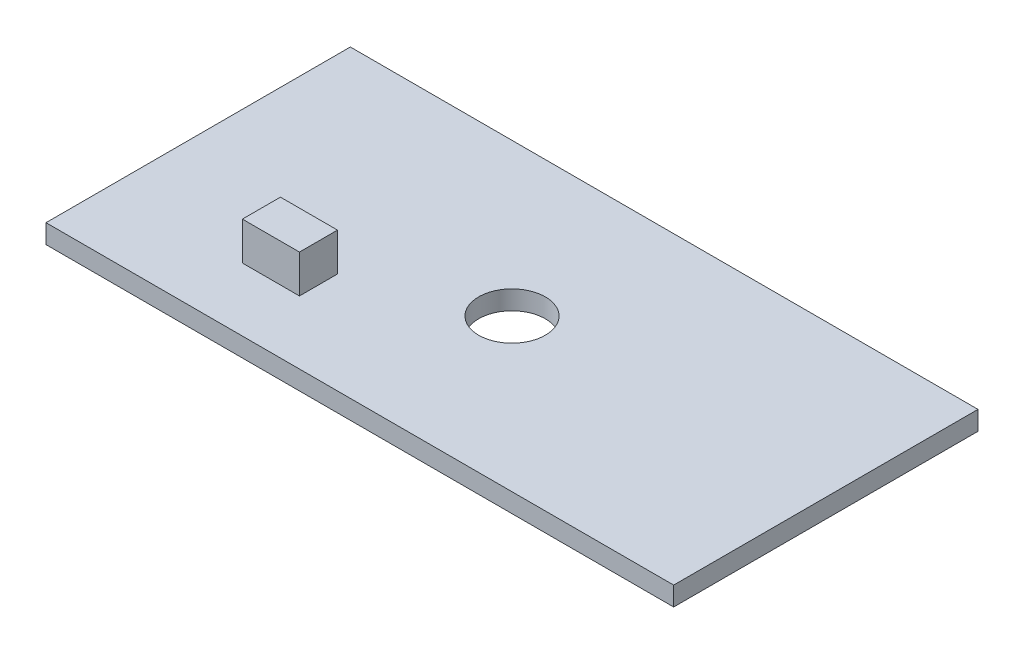
SolidWorks part; units mm, degrees
ref_plane "Спереди" through (0, 0, 0) normal (0, 0, 1) x (1, 0, 0)
ref_plane "Сверху" through (0, 0, 0) normal (0, 1, 0) x (1, 0, 0)
ref_plane "Справа" through (0, 0, 0) normal (1, 0, 0) x (0, 0, -1)
sketch "Эскиз1" plane through (0, 0, 0) normal (0, 1, 0) x (1, 0, 0)
  line L0 (-33, 0) -> (0, 0) construction
  line L1 (0, 8) -> (-33, 8)
  line L2 (0, 8) -> (0, -8)
  line L3 (0, -8) -> (-33, -8)
  line L4 (-33, 8) -> (-33, -8)
  circle A0 centre (-16.5, 0) radius 1.75
  dimension "D3" = 3.5
  dimension "D1" = 16
  dimension "D2" = 33
extrude "Бобышка-Вытянуть1" add sketch "Эскиз1" along normal blind 1
sketch "Эскиз2" plane through (0, 0, 0) normal (0, 1, 0) x (1, 0, 0)
  line L1 (-26, -4.6744) -> (-23, -4.6744)
  line L2 (-26, -4.6744) -> (-26, -2.6744)
  line L3 (-26, -2.6744) -> (-23, -2.6744)
  line L4 (-23, -4.6744) -> (-23, -2.6744)
  dimension "D1" = 2
  dimension "D2" = 3
  dimension "D3" = 10
extrude "Бобышка-Вытянуть2" add sketch "Эскиз2" along normal blind 3
